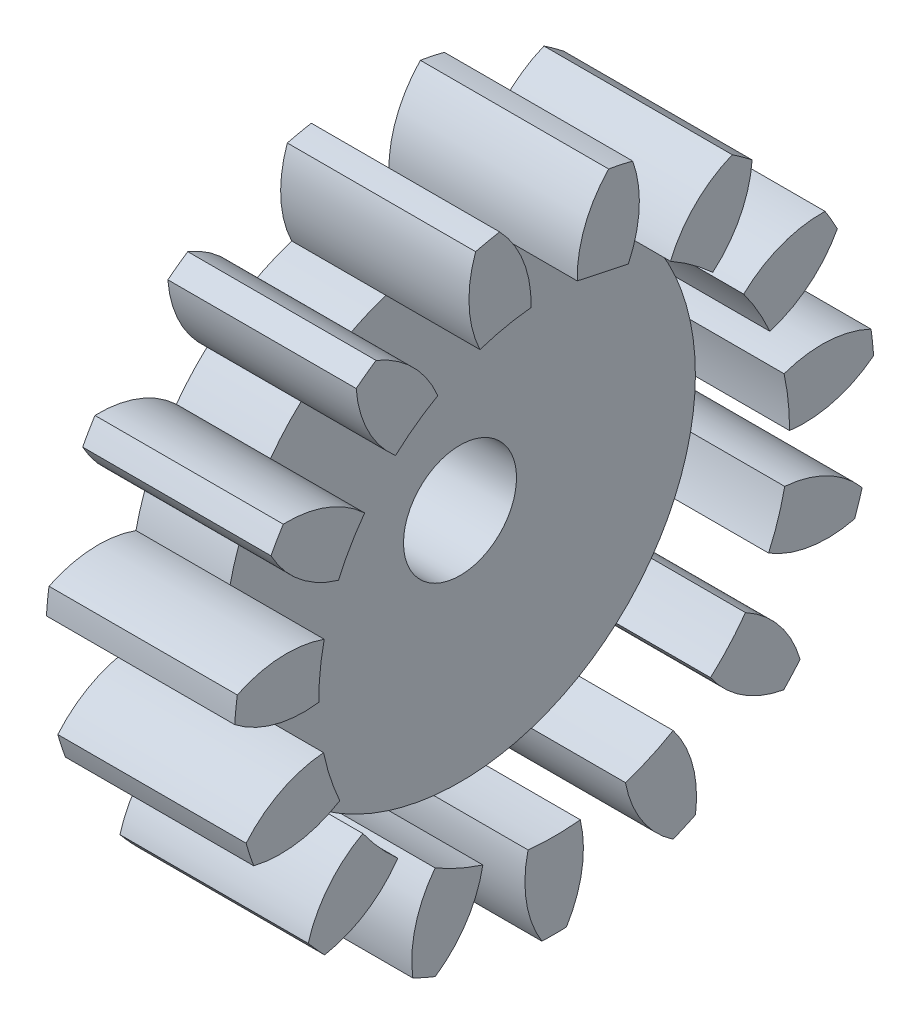
SolidWorks part; units mm, degrees
ref_plane "Plane1" through (0, 0, 0) normal (0, 0, 1) x (1, 0, 0)
ref_plane "Plane2" through (0, 0, 0) normal (0, 1, 0) x (1, 0, 0)
ref_plane "Plane3" through (0, 0, 0) normal (1, 0, 0) x (0, 0, -1)
sketch "HoldingSke" plane through (0, 0, 0) normal (0, 1, 0) x (1, 0, 0)
  line L0 (0, 0) -> (0.483, -0.1294)
  line L1 (-15, 0) -> (100, 0) construction
  line L2 (0, 0) -> (-2.1039, 2.3779)
  line L3 (0, 0) -> (-11.863, 4.5341)
  line L4 (0, 0) -> (8.3417, 2.2352)
  line L5 (0, 0) -> (-46.8476, -17.4728)
  line L6 (0, 0) -> (-4.1448, -2.7965)
  line L7 (-2.1039, 2.3779) -> (8.6586, 51.2059)
  line L8 (-76.2, 54.61) -> (-75.2, 54.61)
  line L9 (-67.7845, 28.3722) -> (-49.3413, 33.142)
  line L10 (-76.2, 71.12) -> (104.1128, 71.12)
  line L11 (0, 0) -> (-5, 0)
  line L12 (-76.2, 101.6) -> (-76.133, 101.6)
  line L13 (24.9733, 27.94) -> (52.9518, 28.4284)
  line L14 (24.9733, 27.94) -> (24.9743, 27.94)
  line L15 (24.9733, 27.94) -> (100.4006, 29.5858)
  line L16 (-63.627, -2) -> (-12.827, -2)
  circle A0 centre (0, 0) radius 3
  circle A1 centre (0, 0) radius 12.499
  circle A2 centre (0, 0) radius 37.5
  circle A3 centre (0, 0) radius 3
  dimension "MHD" = 24.998
  dimension "Hub_dia" = 75
  dimension "Bore" = 6
  dimension "MBD" = 6
  dimension "Num_teeth" = 15
  dimension "Pitch" = 0.5
  dimension "Overall_len" = 50
  dimension "Show_teeth" = 15
  dimension "Thickness" = 5
  dimension "OAL" = 50.0001
  dimension "T_dim" = 1
  dimension "Ap" = 14.5
  dimension "H" = 19.05
  dimension "Pitch_radius" = 180.3128
  dimension "Width" = 5
  dimension "Backlash" = 0.067
  dimension "Addendum_fac" = 1
  dimension "Dedendum_fac" = 1.25
  dimension "Clearance_fac" = 0.25
  dimension "Dedendum_add" = 0.001
  dimension "Module" = 2
sketch "BasProSke" plane through (0, 0, 0) normal (0, 1, 0) x (1, 0, 0)
  line L0 (-10, 0) -> (60, 0) construction
  line L1 (0, 0) -> (0, 17)
  line L2 (0, 0) -> (5, 0)
  line L3 (5, 0) -> (5, 17)
  line L4 (5, 17) -> (0, 17)
  dimension "Thickness" = 5
  dimension "Diameter" = 34
revolve "Base-Revolve" add sketch "BasProSke" angle 360 about L0
sketch "TooCutSke" plane through (0, 0, 0) normal (1, 0, 0) x (0, 0, -1)
  line L1 (0, 0) -> (0, 107) construction
  line L2 (0, 0) -> (-1.6851, 14.905) construction
  line L3 (0, 0) -> (-6.2081, 29.2069) construction
  line L4 (-1.6851, 14.905) -> (-3.1041, 14.6034) construction
  arc A0 (1.2259, 12.4387) -> (-1.2259, 12.4387) centre (0, 0) ccw
  arc A1 (2.9155, 16.7739) -> (-2.9155, 16.7739) centre (0, 0) ccw
  circle A2 centre (0, 0) radius 15 construction
  circle A3 centre (0, 0) radius 14.5222 construction
  arc A4 (-1.2259, 12.4387) -> (-2.9155, 16.7739) centre (-7.2238, 12.5981) ccw
  arc A5 (2.9155, 16.7739) -> (1.2259, 12.4387) centre (7.2238, 12.5981) ccw
  dimension "Root_dia" = 24.998
  dimension "Overcut_dia" = 34.0508
  dimension "Pitch_dia" = 30
  dimension "Base_dia" = 29.0444
  dimension "Flank_rad" = 6
  dimension "Half_ang" = 12
  dimension "Half_CT" = 1.4507
extrude "ToothCut" cut sketch "TooCutSke" along normal through all
fillet "Breaks" [suppressed] radius 0.04
fillet "RootFillets" [suppressed] radius 0.501
pattern_circular "TeethCuts" count 15 every 24 about axis through (-10, 0, 0) along (1, 0, 0) of "ToothCut", "RootFillets", "Breaks"
sketch "HubNeaOneSke" plane through (0, 0, 0) normal (-1, 0, 0) x (0, 0, 1)
  circle A0 centre (0, 0) radius 12.499
  dimension "Diameter" = 24.998
extrude "HubNearOne" [suppressed] add sketch "HubNeaOneSke" along normal blind 45.0001
sketch "HubNeaBotSke" plane through (0, 0, 0) normal (-1, 0, 0) x (0, 0, 1)
  circle A0 centre (0, 0) radius 12.499
  dimension "Diameter" = 24.998
extrude "HubNearBoth" [suppressed] add sketch "HubNeaBotSke" along normal blind 22.5
ref_plane "FarPln" through (5, 0, 0) normal (1, 0, 0) x (0, 0, -1)
sketch "HubFarSke" plane through (5, 0, 0) normal (1, 0, 0) x (0, 0, -1)
  circle A0 centre (0, 0) radius 12.499
  dimension "Diameter" = 24.998
extrude "HubFar" [suppressed] add sketch "HubFarSke" along normal blind 22.5
sketch "BorSke" plane through (0, 0, 0) normal (1, 0, 0) x (0, 0, -1)
  circle A0 centre (0, 0) radius 3
  dimension "Diameter" = 6
extrude "Bore" cut sketch "BorSke" along normal mid plane 100.0001
sketch "KeySke" plane through (0, 0, 0) normal (1, 0, 0) x (0, 0, -1)
  line L0 (-1, 0) -> (-1, 4)
  line L1 (-1, 4) -> (1, 4)
  line L2 (1, 4) -> (1, 0)
  line L3 (0, 0) -> (0, 34) construction
  line L4 (-1, 0) -> (1, 0)
  dimension "Offset" = 4
  dimension "Width" = 2
extrude "Keyway" [suppressed] cut sketch "KeySke" along normal mid plane 100.0001
pattern_circular "Keyway2" [suppressed] count 2 every 90 about axis through (-10, 0, 0) along (1, 0, 0)
sketch "Sketch1" plane through (5, 0, 0) normal (1, 0, 0) x (0, 0, -1)
  line L0 (1.2259, 12.4387) -> (3.9393, 11.862)
  line L1 (6.1792, 10.8647) -> (8.4235, 9.2342)
  line L2 (10.0641, 7.4121) -> (11.4511, 5.0097)
  line L3 (12.2088, 2.6778) -> (12.4987, -0.081)
  line L4 (12.2424, -2.5194) -> (11.3852, -5.1577)
  line L5 (10.1593, -7.2811) -> (8.3031, -9.3426)
  line L6 (6.3195, -10.7837) -> (3.7853, -11.912)
  line L7 (1.387, -12.4218) -> (-1.387, -12.4218)
  line L8 (-3.7853, -11.912) -> (-6.3195, -10.7837)
  line L9 (-8.3031, -9.3426) -> (-10.1593, -7.2811)
  line L10 (-11.3852, -5.1577) -> (-12.2424, -2.5194)
  line L11 (-12.4987, -0.081) -> (-12.2088, 2.6778)
  line L12 (-11.4511, 5.0097) -> (-10.0641, 7.4121)
  line L13 (-8.4235, 9.2342) -> (-6.1792, 10.8647)
  line L14 (-3.9393, 11.862) -> (-1.2259, 12.4387)
  circle A0 centre (0, 0) radius 12.5
  arc A1 (2.8942, 16.7518) -> (1.2259, 12.4387) centre (7.2238, 12.5981) ccw construction
  arc A2 (2.8942, 16.7518) -> (1.2259, 12.4387) centre (7.2238, 12.5981) ccw
  arc A3 (4.1696, 16.4807) -> (2.8942, 16.7518) centre (0, 0) ccw construction
  arc A4 (4.1696, 16.4807) -> (2.8942, 16.7518) centre (0, 0) ccw
  arc A5 (3.9393, 11.862) -> (4.1696, 16.4807) centre (-1.4752, 14.4471) ccw construction
  arc A6 (3.9393, 11.862) -> (4.1696, 16.4807) centre (-1.4752, 14.4471) ccw
  arc A7 (8.4235, 9.2342) -> (10.5125, 13.3599) centre (4.5285, 13.7981) ccw
  arc A8 (10.5125, 13.3599) -> (9.4575, 14.1264) centre (0, 0) ccw
  arc A9 (9.4575, 14.1264) -> (6.1792, 10.8647) centre (11.7234, 8.5707) ccw
  arc A10 (11.4511, 5.0097) -> (15.0376, 7.9291) centre (9.7492, 10.7633) ccw
  arc A11 (15.0376, 7.9291) -> (14.3856, 9.0584) centre (0, 0) ccw
  arc A12 (14.3856, 9.0584) -> (10.0641, 7.4121) centre (14.1959, 3.0614) ccw
  arc A13 (12.4987, -0.081) -> (16.9626, 1.1273) centre (13.2841, 5.8674) ccw
  arc A14 (16.9626, 1.1273) -> (16.8263, 2.4241) centre (0, 0) ccw
  arc A15 (16.8263, 2.4241) -> (12.2088, 2.6778) centre (14.2137, -2.9773) ccw
  arc A16 (11.3852, -5.1577) -> (15.9546, -5.8695) centre (14.5222, -0.043) ccw
  arc A17 (15.9546, -5.8695) -> (16.3575, -4.6293) centre (0, 0) ccw
  arc A18 (16.3575, -4.6293) -> (12.2424, -2.5194) centre (11.7739, -8.5011) ccw
  arc A19 (8.3031, -9.3426) -> (12.1879, -11.8514) centre (13.2492, -5.946) ccw
  arc A20 (12.1879, -11.8514) -> (13.0604, -10.8823) centre (0, 0) ccw
  arc A21 (13.0604, -10.8823) -> (10.1593, -7.2811) centre (7.2983, -12.555) ccw
  arc A22 (3.7853, -11.912) -> (6.3138, -15.784) centre (9.6853, -10.8208) ccw
  arc A23 (6.3138, -15.784) -> (7.5051, -15.2537) centre (0, 0) ccw
  arc A24 (7.5051, -15.2537) -> (6.3195, -10.7837) centre (1.5607, -14.4381) ccw
  arc A25 (-1.387, -12.4218) -> (-0.652, -16.9875) centre (4.4467, -13.8247) ccw
  arc A26 (-0.652, -16.9875) -> (0.652, -16.9875) centre (0, 0) ccw
  arc A27 (0.652, -16.9875) -> (1.387, -12.4218) centre (-4.4467, -13.8247) ccw
  arc A28 (-6.3195, -10.7837) -> (-7.5051, -15.2537) centre (-1.5607, -14.4381) ccw
  arc A29 (-7.5051, -15.2537) -> (-6.3138, -15.784) centre (0, 0) ccw
  arc A30 (-6.3138, -15.784) -> (-3.7853, -11.912) centre (-9.6853, -10.8208) ccw
  arc A31 (-10.1593, -7.2811) -> (-13.0604, -10.8823) centre (-7.2983, -12.555) ccw
  arc A32 (-13.0604, -10.8823) -> (-12.1879, -11.8514) centre (0, 0) ccw
  arc A33 (-12.1879, -11.8514) -> (-8.3031, -9.3426) centre (-13.2492, -5.946) ccw
  arc A34 (-12.2424, -2.5194) -> (-16.3575, -4.6293) centre (-11.7739, -8.5011) ccw
  arc A35 (-16.3575, -4.6293) -> (-15.9546, -5.8695) centre (0, 0) ccw
  arc A36 (-15.9546, -5.8695) -> (-11.3852, -5.1577) centre (-14.5222, -0.043) ccw
  arc A37 (-12.2088, 2.6778) -> (-16.8263, 2.4241) centre (-14.2137, -2.9773) ccw
  arc A38 (-16.8263, 2.4241) -> (-16.9626, 1.1273) centre (0, 0) ccw
  arc A39 (-16.9626, 1.1273) -> (-12.4987, -0.081) centre (-13.2841, 5.8674) ccw
  arc A40 (-10.0641, 7.4121) -> (-14.3856, 9.0584) centre (-14.1959, 3.0614) ccw
  arc A41 (-14.3856, 9.0584) -> (-15.0376, 7.9291) centre (0, 0) ccw
  arc A42 (-15.0376, 7.9291) -> (-11.4511, 5.0097) centre (-9.7492, 10.7633) ccw
  arc A43 (-6.1792, 10.8647) -> (-9.4575, 14.1264) centre (-11.7234, 8.5707) ccw
  arc A44 (-9.4575, 14.1264) -> (-10.5125, 13.3599) centre (0, 0) ccw
  arc A45 (-10.5125, 13.3599) -> (-8.4235, 9.2342) centre (-4.5285, 13.7981) ccw
  arc A46 (-1.2259, 12.4387) -> (-2.8942, 16.7518) centre (-7.2238, 12.5981) ccw
  arc A47 (-2.8942, 16.7518) -> (-4.1696, 16.4807) centre (0, 0) ccw
  arc A48 (-4.1696, 16.4807) -> (-3.9393, 11.862) centre (1.4752, 14.4471) ccw
  dimension "D1" = 15
extrude "Boss-Extrude1" add sketch "Sketch1" along normal blind 5 contours A8 A9 A0 A7 | A11 A12 A0 A10 | A14 A15 A0 A13 | A17 A18 A0 A16 | A20 A21 A0 A19 | A23 A24 A0 A22 | A26 A27 A0 A25 | A29 A30 A0 A28 | A32 A33 A0 A31 | A35 A36 A0 A34 | A38 A39 A0 A37 | A41 A42 A0 A40 | A44 A45 A0 A43 | A47 A48 A0 A46 | L0 A6 A4 A2
equation "' \"Module@HoldingSke\" = 6.35"
equation "' \"Num_teeth@HoldingSke\" = 12"
equation "' \"Ap@HoldingSke\" =  20"
equation "' \"Ap@HoldingSke\" = 20"
equation "' \"Width@HoldingSke\" = 0.5 * 25.4"
equation "' \"Hub_dia@HoldingSke\"= 1 * 25.4"
equation "' \"Hub_dia@HoldingSke\" = 1 * 25.4"
equation "' \"Overall_len@HoldingSke\" = 1.0 * 25.4"
equation "' \"Bore@HoldingSke\" = 0.75 * 25.4"
equation "' \"T_dim@HoldingSke\" = 0.1 * 25.4"
equation "' \"Width@KeySke\" = 0.25 * 25.4"
equation "' \"Show_teeth@HoldingSke\" = 13"
equation "' \"Backlash@HoldingSke\" = 0.009 * 25.4"
equation "' \"Addendum_fac@HoldingSke\" = 1.0"
equation "' \"Dedendum_fac@HoldingSke\" = 1.25"
equation "' \"Dedendum_add@HoldingSke\" = 0.00005 * 25.4"
equation "' \"Clearance_fac@HoldingSke\" = 0.25"
equation "\"Pitch@HoldingSke\" = 1 / \"Module@HoldingSke\""
equation "\"Overcut_dia@TooCutSke\" = (\"Num_teeth@HoldingSke\" + 2 * \"Addendum_fac@HoldingSke\") / \"Pitch@HoldingSke\" + 0.002 * 25.4"
equation "\"Pitch_dia@TooCutSke\" = \"Num_teeth@HoldingSke\" / \"Pitch@HoldingSke\""
equation "\"Base_dia@TooCutSke\" = \"Num_teeth@HoldingSke\" / \"Pitch@HoldingSke\" * cos((\"Ap@HoldingSke\"  * 3.14159265 / 180))"
equation "\"Root_dia@TooCutSke\" = (\"Num_teeth@HoldingSke\" + 2) / \"Pitch@HoldingSke\" - 2 * (\"Addendum_fac@HoldingSke\" + \"Dedendum_fac@HoldingSke\") / \"Pitch@HoldingSke\" - \"Dedendum_add@HoldingSke\" * 2"
equation "\"Half_ang@TooCutSke\" = 180 / \"Num_teeth@HoldingSke\""
equation "\"Half_CT@TooCutSke\" = \"Num_teeth@HoldingSke\" / \"Pitch@HoldingSke\" * sin((3.14159265 / 2 / \"Num_teeth@HoldingSke\")) / 2 - 7 * \"Backlash@HoldingSke\" / 4"
equation "\"Flank_rad@TooCutSke\" = \"Num_teeth@HoldingSke\" / \"Pitch@HoldingSke\" / 5"
equation "\"Radius@RootFillets\" = \"Clearance_fac@HoldingSke\" / \"Pitch@HoldingSke\" + \"Dedendum_add@HoldingSke\""
equation "\"Break_rad@Breaks\" = 0.02 / \"Pitch@HoldingSke\""
equation "\"Thickness@HoldingSke\" = \"Width@HoldingSke\""
equation "\"OAL@HoldingSke\" = \"Thickness@HoldingSke\""
equation "\"MHD@HoldingSke\" = (\"Num_teeth@HoldingSke\" + 2) / \"Pitch@HoldingSke\" - 2 * (\"Addendum_fac@HoldingSke\" + \"Dedendum_fac@HoldingSke\")  / \"Pitch@HoldingSke\" - \"Dedendum_add@HoldingSke\" * 2"
equation "\"MBD@HoldingSke\" = (\"Num_teeth@HoldingSke\" + 2) / \"Pitch@HoldingSke\" - 2 * (\"Addendum_fac@HoldingSke\" + \"Dedendum_fac@HoldingSke\")  / \"Pitch@HoldingSke\" - \"Dedendum_add@HoldingSke\" * 2 - 0.002 * 25.4"
equation "\"MHD@HoldingSke\" = ((sgn( \"MHD@HoldingSke\" - \"Hub_dia@HoldingSke\" )-1)*( \"MHD@HoldingSke\" - \"Hub_dia@HoldingSke\" ))/-2+ \"Hub_dia@HoldingSke\""
equation "\"MBD@HoldingSke\" = ((sgn( \"MBD@HoldingSke\" - \"Bore@HoldingSke\" )-1)*( \"MBD@HoldingSke\" - \"Bore@HoldingSke\" ))/-2+ \"Bore@HoldingSke\""
equation "\"OAL@HoldingSke\" = ((sgn( \"OAL@HoldingSke\" - \"Overall_len@HoldingSke\" )+1)*( \"OAL@HoldingSke\" - \"Overall_len@HoldingSke\" ))/2 + \"Overall_len@HoldingSke\" + 0.000002 * 25.4"
equation "\"Num_teeth@TeethCuts\" = int( \"Show_teeth@HoldingSke\" ) + 1"
equation "\"Num_teeth@TeethCuts\" = ((sgn( \"Num_teeth@TeethCuts\" - \"Num_teeth@HoldingSke\" )-1)*( \"Num_teeth@TeethCuts\" - \"Num_teeth@HoldingSke\" ))/-2+ \"Num_teeth@HoldingSke\""
equation "\"Num_teeth@TeethCuts\" = ((sgn( \"Num_teeth@TeethCuts\" - 2.0)+1)*( \"Num_teeth@TeethCuts\" - 2.0))/2 +2.0"
equation "\"Angle@TeethCuts\" = 360.0 / \"Num_teeth@HoldingSke\""
equation "\"Diameter@BasProSke\" = (\"Num_teeth@HoldingSke\" + 2 * \"Addendum_fac@HoldingSke\") / \"Pitch@HoldingSke\""
equation "\"Thickness@BasProSke\"  = \"Thickness@HoldingSke\""
equation "' \"Fillet_rad@BasProSke\" =  \"Thickness@HoldingSke\" * 0.05"
equation "' \"Fillet_rad@BasProSke\" = \"Thickness@HoldingSke\" * 0.05"
equation "\"MHD@HoldingSke\" = ((sgn( \"MHD@HoldingSke\" - \"Root_dia@TooCutSke\" )-1)*( \"MHD@HoldingSke\" - \"Root_dia@TooCutSke\" ))/-2+ \"Root_dia@TooCutSke\""
equation "\"Diameter@HubNeaOneSke\" = \"MHD@HoldingSke\""
equation "\"Length@HubNearOne\" = \"OAL@HoldingSke\" - \"Thickness@BasProSke\""
equation "\"Diameter@HubNeaBotSke\" = \"MHD@HoldingSke\""
equation "\"Length@HubNearBoth\" = ( \"OAL@HoldingSke\" - \"Thickness@BasProSke\" ) / 2.0"
equation "\"Thickness@FarPln\" = \"Thickness@BasProSke\""
equation "\"Diameter@HubFarSke\" = \"MHD@HoldingSke\""
equation "\"Length@HubFar\" = ( \"OAL@HoldingSke\" - \"Thickness@BasProSke\" ) / 2.0"
equation "\"Diameter@BorSke\" = \"MBD@HoldingSke\""
equation "\"D1@Bore\" = \"OAL@HoldingSke\" * 2.0"
equation "\"D1@Keyway\" = \"OAL@HoldingSke\" * 2.0"
equation "\"Offset@KeySke\" = \"T_dim@HoldingSke\" + \"MBD@HoldingSke\" / 2.0"
